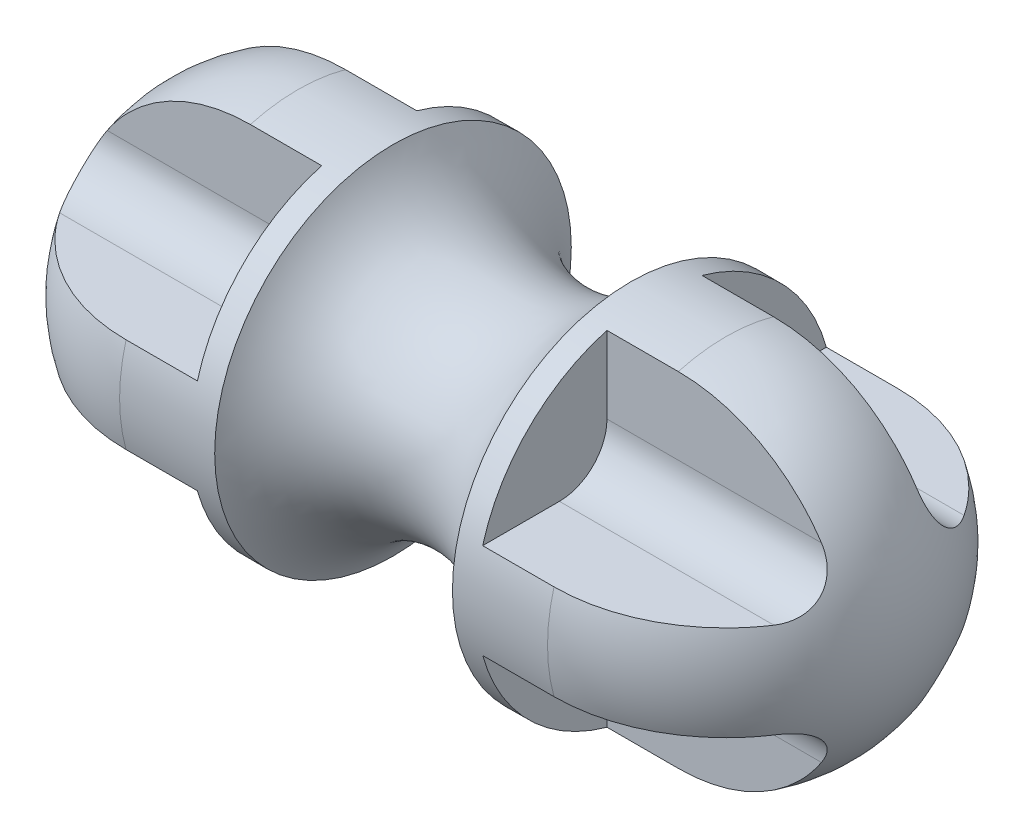
SolidWorks part; units mm, degrees
ref_plane "前视基准面" through (0, 0, 0) normal (0, 0, 1) x (1, 0, 0)
ref_plane "上视基准面" through (0, 0, 0) normal (0, 1, 0) x (1, 0, 0)
ref_plane "右视基准面" through (0, 0, 0) normal (1, 0, 0) x (0, 0, -1)
sketch "草图1" plane through (0, 0, 0) normal (0, 1, 0) x (1, 0, 0)
  line L0 (0, 0) -> (25, 0)
  line L5 (0, 0) -> (-82.5, 0)
  line L6 (0, 0) -> (0, 37.5)
  line L7 (-25, 37.5) -> (-45, 37.5)
  line L9 (25, 0) -> (25, 37.5)
  line L11 (-25, 37.5) -> (-25, 0)
  line L12 (-30, 37.5) -> (-30, 0)
  arc A1 (-45, 37.5) -> (-82.5, 0) centre (-45, 0) ccw
  arc A2 (-25, 37.5) -> (25, 37.5) centre (0, 50.8333) ccw
  point P14 (0, 66.9874)
  dimension "D3" = 75
  dimension "D1" = 82.5
  dimension "D4" = 25
  dimension "D5" = 25
  dimension "D6" = 5
revolve "旋转1" add sketch "草图1" angle 360 about L5
ref_plane "基准面1" through (-30, 0, 0) normal (1, 0, 0) x (0, 0, -1)
sketch "草图2" plane through (-30, 0, 0) normal (1, 0, 0) x (0, 0, -1)
  line L0 (10, 54.7556) -> (54.446, 54.7556)
  line L4 (10, 54.7556) -> (10, 20)
  line L5 (54.446, 54.7556) -> (54.446, 10)
  line L6 (-10, -54.7556) -> (10, 54.7556) construction
  line L12 (0, 0) -> (54.446, 10) construction
  line L13 (20, 10) -> (54.446, 10)
  arc A0 (20, 10) -> (10, 20) centre (20, 20) cw
  point P0 (0, 0)
  point P6 (0, 0)
  dimension "D1" = 10
extrude "切除-拉伸1" cut sketch "草图2" against normal through all contours L5 L13 A0 L4 L0
pattern_circular "阵列(圆周)1" count 4 over 360 about axis through (0, 0, 0) along (1, 0, 0) of "切除-拉伸1"
mirror "镜向2" about plane through (0, 0, 0) normal (1, 0, 0) of "阵列(圆周)1", "旋转1", "切除-拉伸1"
